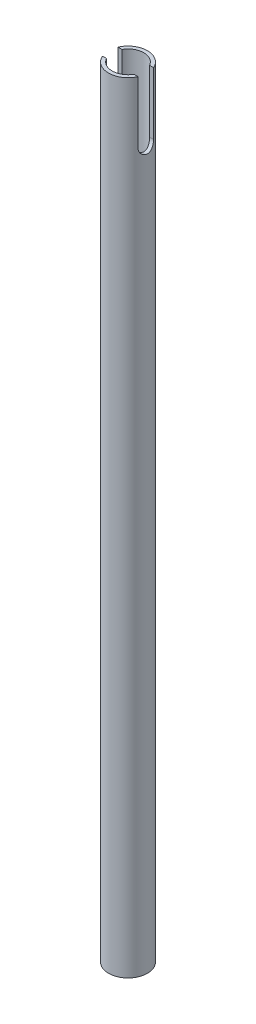
SolidWorks part; units mm, degrees
material "AISI 4130 Steel, annealed at 865C"
ref_plane "X-Y Datum" through (0, 0, 0) normal (0, 0, 1) x (1, 0, 0)
ref_plane "X-Z Datum" through (0, 0, 0) normal (0, 1, 0) x (1, 0, 0)
ref_plane "Y-Z Datum" through (0, 0, 0) normal (1, 0, 0) x (0, 0, -1)
sketch "Sketch1" plane through (0, 0, 0) normal (0, 1, 0) x (1, 0, 0)
  circle A0 centre (0, 0) radius 7.9375
  circle A1 centre (0, 0) radius 6.4643
  dimension "D1" = 15.875
  dimension "D2" = 1.4732
extrude "Boss-Extrude1" add sketch "Sketch1" along normal offset from surface (318.5477 mm away) 25.4
sketch "Sketch4" plane through (0, 0, 0) normal (1, 0, 0) x (0, 0, -1)
  line L5 (0, 343.9477) -> (0, 293.1477) construction
  line L6 (7.9375, 318.5477) -> (-7.9375, 318.5477) construction
  line L7 (3.175, 343.9477) -> (3.175, 293.1477)
  line L8 (-3.175, 343.9477) -> (-3.175, 293.1477)
  arc A0 (3.175, 343.9477) -> (-3.175, 343.9477) centre (0, 343.9477) ccw
  arc A1 (-3.175, 293.1477) -> (3.175, 293.1477) centre (0, 293.1477) ccw
  point P4 (0, 318.5477)
  dimension "D1" = 6.35
  dimension "D2" = 25.4
extrude "Cut-Extrude1" cut sketch "Sketch4" against normal through all both and the other way through all
